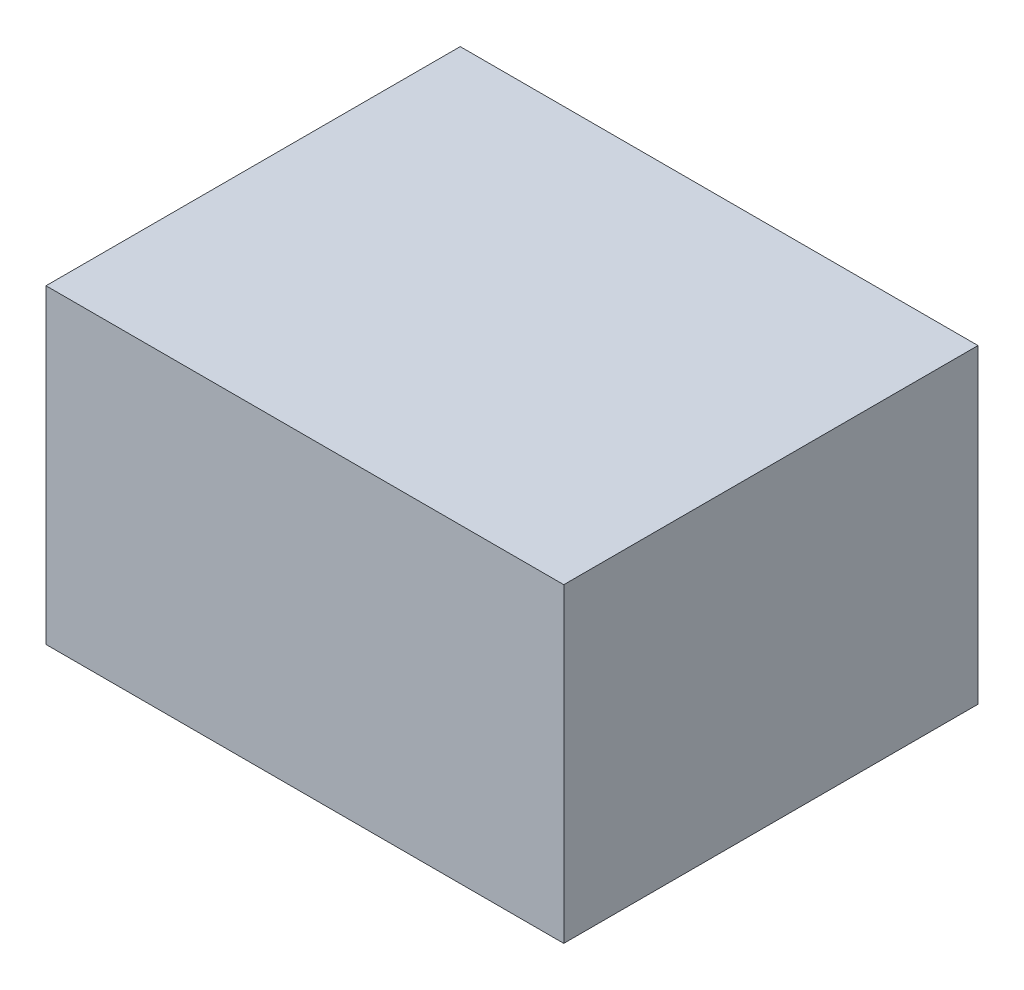
SolidWorks part; units mm, degrees
ref_plane "前视基准面" through (0, 0, 0) normal (0, 0, 1) x (1, 0, 0)
ref_plane "上视基准面" through (0, 0, 0) normal (0, 1, 0) x (1, 0, 0)
ref_plane "右视基准面" through (0, 0, 0) normal (1, 0, 0) x (0, 0, -1)
sketch "草图1" plane through (0, 0, 0) normal (0, 1, 0) x (1, 0, 0)
  line L1 (-100, 200) -> (150, 200)
  line L2 (-100, 200) -> (-100, 0)
  line L3 (-100, 0) -> (150, 0)
  line L4 (150, 200) -> (150, 0)
  dimension "D1" = 250
  dimension "D2" = 200
extrude "凸台-拉伸1" add sketch "草图1" along normal blind 150
